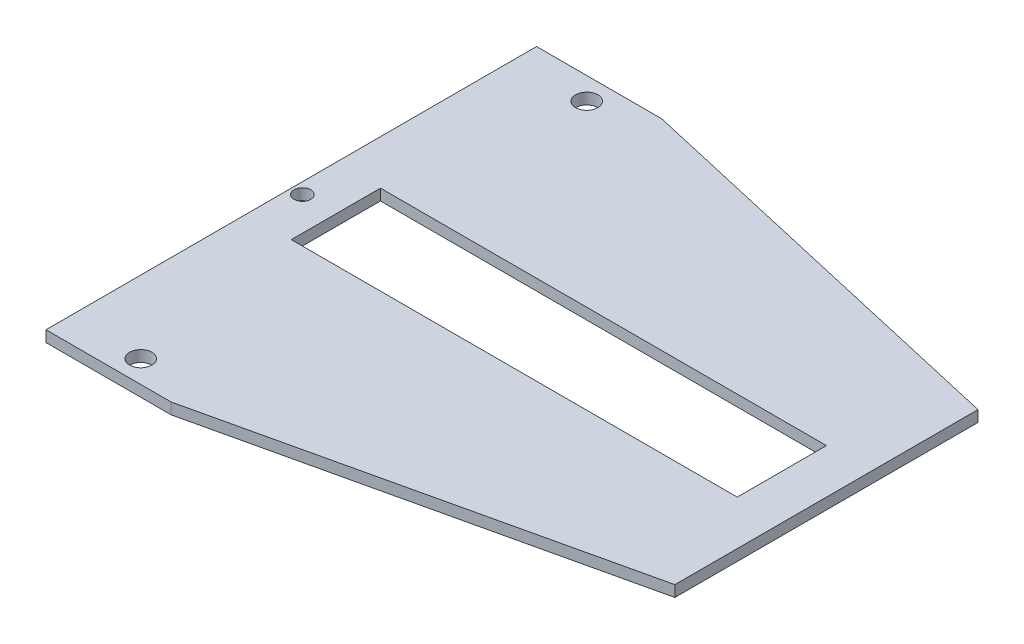
SolidWorks part; units mm, degrees
material "ASTM A36 Steel"
ref_plane "Front Plane" through (0, 0, 0) normal (0, 0, 1) x (1, 0, 0)
ref_plane "Top Plane" through (0, 0, 0) normal (0, 1, 0) x (1, 0, 0)
ref_plane "Right Plane" through (0, 0, 0) normal (1, 0, 0) x (0, 0, -1)
sketch "Sketch1" plane through (0, 0, 0) normal (0, 1, 0) x (1, 0, 0)
  line L0 (0, -86.3247) -> (0, -139.7)
  line L1 (0, 0) -> (304.8, 0) construction
  line L2 (0, 86.3247) -> (0, 6.35)
  line L3 (0, -86.3247) -> (304.8, -86.3247) construction
  line L4 (304.8, 86.3247) -> (304.8, -86.3247)
  line L5 (0, -139.7) -> (71.283, -139.7)
  line L6 (71.283, -139.7) -> (304.8, -86.3247)
  line L7 (279.4, 25.4) -> (279.4, -25.4)
  line L8 (279.4, -25.4) -> (25.4, -25.4)
  line L9 (25.4, -25.4) -> (25.4, -6.35)
  line L10 (0, 86.3247) -> (0, 139.7)
  line L11 (0, 139.7) -> (71.283, 139.7)
  line L12 (71.283, 139.7) -> (304.8, 86.3247)
  line L13 (279.4, 25.4) -> (25.4, 25.4)
  line L14 (0, -6.35) -> (0, -86.3247)
  line L16 (0, 6.35) -> (0, -6.35)
  line L18 (25.4, 6.35) -> (25.4, 25.4)
  line L19 (25.4, 6.35) -> (25.4, -6.35)
  circle A0 centre (41.2732, -127) radius 6.35
  circle A1 centre (41.2732, 127) radius 6.35
  circle A2 centre (6.3482, 0) radius 4.7625
  point P21 (279.4, 0)
  point P22 (25.4, 0)
  dimension "D3" = 139.7
  dimension "D4" = 71.283
  dimension "D5" = 12.7
  dimension "D6" = 12.7
  dimension "D12" = 12.7
  dimension "D16" = 9.525
  dimension "D17" = 6.3482
  dimension "D1" = 304.8
  dimension "D2" = 86.3247
  dimension "D7" = 30.0097
  dimension "D8" = 25.4
  dimension "D9" = 25.4
  dimension "D10" = 254
  dimension "D11" = 90
  dimension "D13" = 12.7
  dimension "D14" = 6.35
  dimension "D15" = 6.35
extrude "Boss-Extrude1" add sketch "Sketch1" along normal blind 6.35
